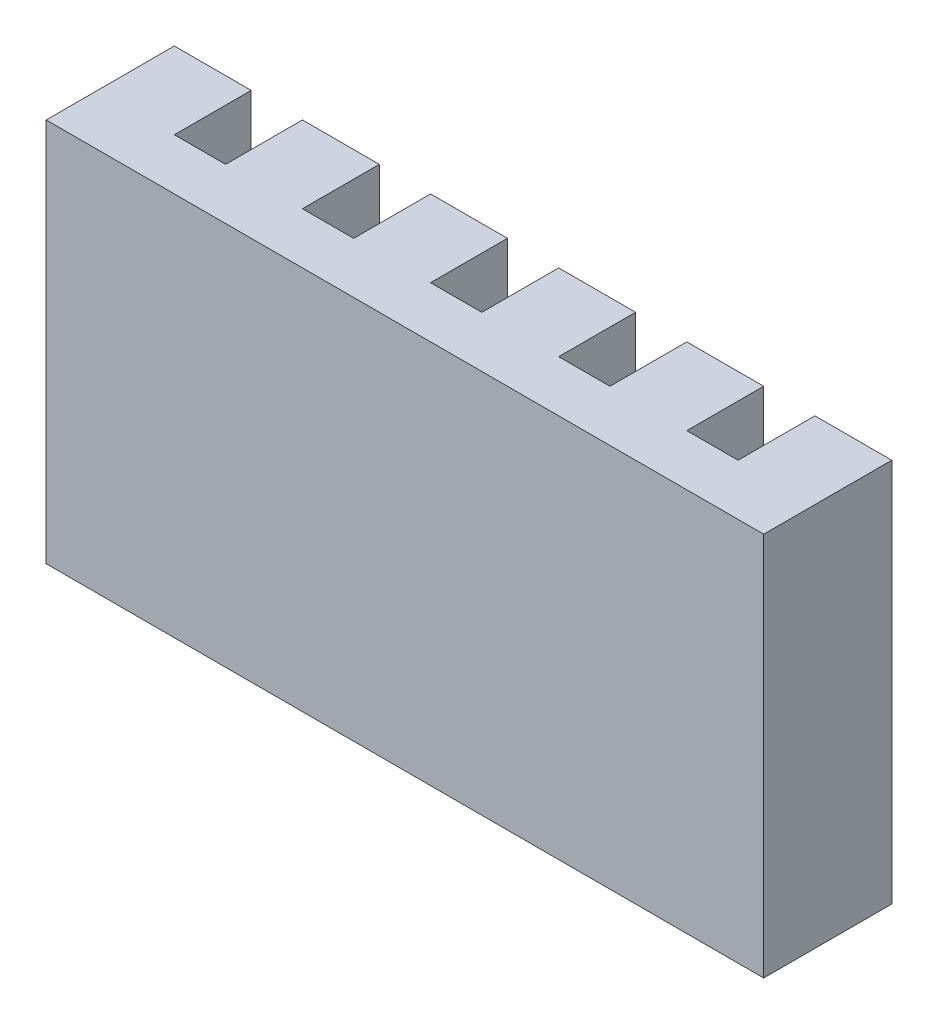
SolidWorks part; units mm, degrees
ref_plane "Front Plane" through (0, 0, 0) normal (0, 0, 1) x (1, 0, 0)
ref_plane "Top Plane" through (0, 0, 0) normal (0, 1, 0) x (1, 0, 0)
ref_plane "Right Plane" through (0, 0, 0) normal (1, 0, 0) x (0, 0, -1)
sketch "Sketch3" plane through (0, 0, 0) normal (0, 1, 0) x (1, 0, 0)
  line L0 (-14, 0) -> (14, 0)
  line L1 (14, 0) -> (14, 5)
  line L2 (14, 5) -> (11, 5)
  line L3 (11, 5) -> (11, 2)
  line L4 (11, 2) -> (9, 2)
  line L5 (9, 2) -> (9, 5)
  line L6 (-1, 2) -> (1, 2)
  line L7 (1, 2) -> (1, 5)
  line L8 (1, 5) -> (4, 5)
  line L9 (4, 5) -> (4, 2)
  line L10 (4, 2) -> (6, 2)
  line L11 (6, 2) -> (6, 5)
  line L12 (6, 5) -> (9, 5)
  line L13 (0, 2) -> (0, 0) construction
  line L14 (-1, 2) -> (-1, 5)
  line L15 (-1, 5) -> (-4, 5)
  line L16 (-4, 5) -> (-4, 2)
  line L17 (-4, 2) -> (-6, 2)
  line L18 (-6, 2) -> (-6, 5)
  line L19 (-6, 5) -> (-9, 5)
  line L20 (-9, 5) -> (-9, 2)
  line L21 (-9, 2) -> (-11, 2)
  line L22 (-11, 2) -> (-11, 5)
  line L23 (-11, 5) -> (-14, 5)
  line L24 (-14, 5) -> (-14, 0)
  point P4 (0, 0)
  point P29 (0, 0)
  dimension "D1" = 2
  dimension "D2" = 3
  dimension "D3" = 3
  dimension "D4" = 2
extrude "Boss-Extrude4" add sketch "Sketch3" along normal mid plane 15
